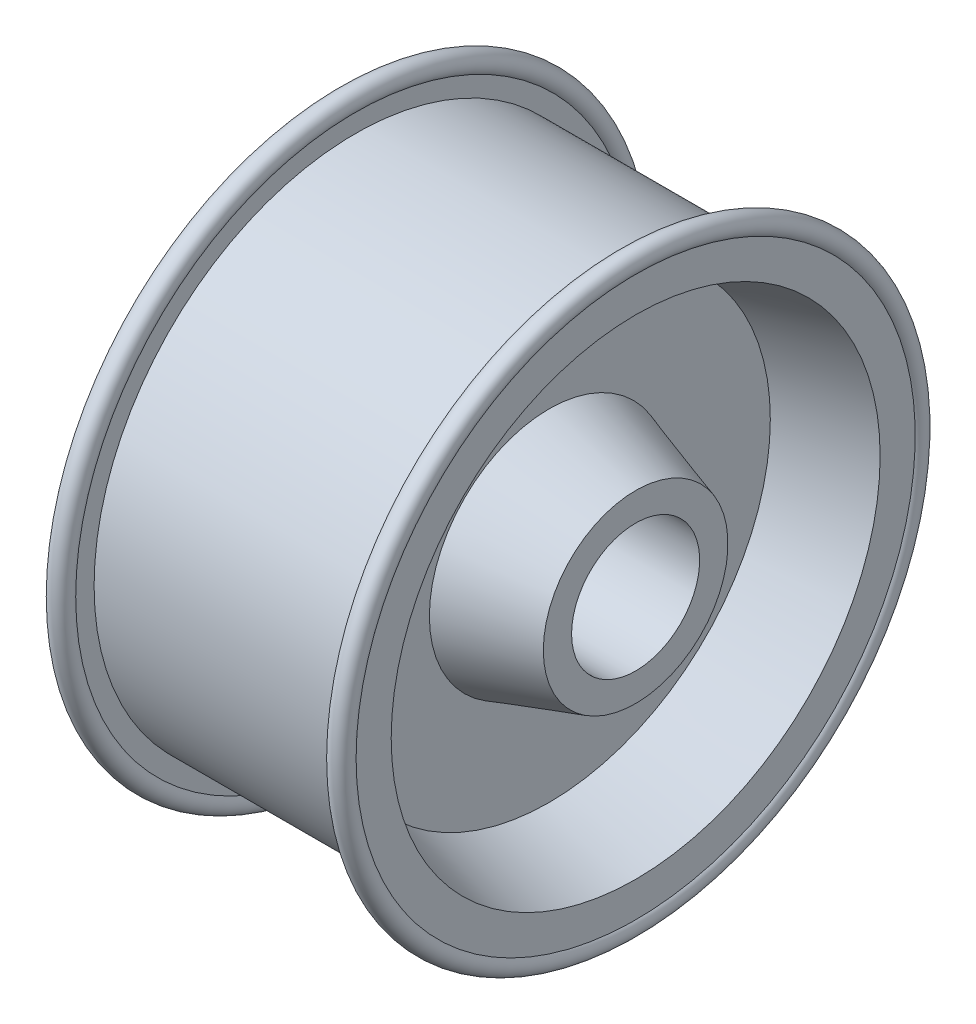
SolidWorks part; units mm, degrees
ref_plane "Front Plane" through (0, 0, 0) normal (0, 0, 1) x (1, 0, 0)
ref_plane "Top Plane" through (0, 0, 0) normal (0, 1, 0) x (1, 0, 0)
ref_plane "Right Plane" through (0, 0, 0) normal (1, 0, 0) x (0, 0, -1)
sketch "Sketch1" plane through (0, 0, 0) normal (0, 0, 1) x (1, 0, 0)
  line L0 (-841.8731, 0) -> (41251.7827, 0) construction
  line L1 (0, -841.8731) -> (0, 41251.7827) construction
  line L2 (-38.1, 16.5404) -> (38.1, 16.5404)
  line L3 (38.1, 16.5404) -> (38.1, 23.841)
  line L4 (38.1, 23.841) -> (15.7419, 30.9135)
  line L5 (15.7419, 30.9135) -> (15.7419, 57.15)
  line L6 (15.7419, 57.15) -> (38.114, 63.1446)
  line L7 (38.114, 63.1446) -> (38.114, 72.2075)
  line L8 (-38.114, 63.1446) -> (-38.114, 72.2075)
  line L9 (34.3064, 72.2075) -> (34.3064, 67.4603)
  line L10 (34.3064, 67.4603) -> (-34.3064, 67.4603)
  line L11 (-15.7419, 57.15) -> (-38.114, 63.1446)
  line L12 (-38.1, 23.841) -> (-15.7419, 30.9135)
  line L13 (-38.1, 16.5404) -> (-38.1, 23.841)
  line L14 (-34.3064, 72.2075) -> (-34.3064, 67.4603)
  line L15 (-15.7419, 30.9135) -> (-15.7419, 57.15)
  arc A0 (34.3064, 72.2075) -> (38.114, 72.2075) centre (36.2102, 74.1113) cw
  arc A1 (-34.3064, 72.2075) -> (-38.114, 72.2075) centre (-36.2102, 74.1113) ccw
  point P20 (0, 67.4603)
  point P25 (0, 16.5404)
  dimension "D3" = 5.3848
  dimension "D1" = 38.1
  dimension "D2" = 15
  dimension "D4" = 4.7472
revolve "Revolve4" add sketch "Sketch1" angle 360 about L0
sketch "Sketch2" plane through (15.7419, 0, 0) normal (1, 0, 0) x (0, 0, -1)
  circle A0 centre (0, 0) radius 44.45 construction
  point P6 (0, 44.45)
  dimension "D1" = 88.9
hole_wizard "3/8 (0.3) Diameter Hole3" positions "Sketch2" profile "Sketch6" hole size "3/8" standard "ANSI Inch" end condition through all
sketch "Sketch6" plane through (15.7419, 44.45, 0) normal (0, 1, 0) x (0, 0, -1)
  line L0 (0, 0) -> (0, 54.6445)
  line L1 (0, 54.6445) -> (3.81, 54.6445)
  line L2 (3.81, 54.6445) -> (3.81, 0)
  line L5 (3.81, 0) -> (0, 0)
  line L11 (0, -6.35) -> (0, 107.95) construction
  dimension "Thru Hole Dia." = 7.62
  dimension "Thru Hole Depth" = 54.6445
